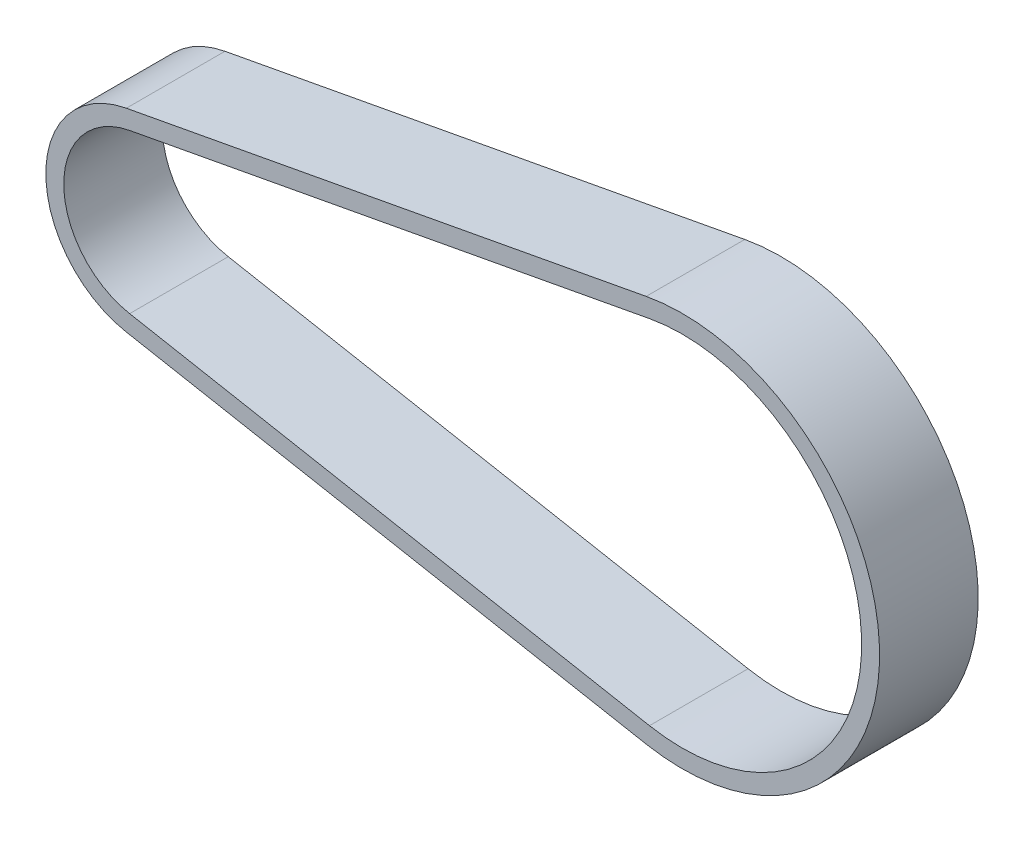
SolidWorks part; units mm, degrees
material "EPDM 60 硬度计"
ref_plane "前视基准面" through (0, 0, 0) normal (0, 0, 1) x (1, 0, 0)
ref_plane "上视基准面" through (0, 0, 0) normal (0, 1, 0) x (1, 0, 0)
ref_plane "右视基准面" through (0, 0, 0) normal (1, 0, 0) x (0, 0, -1)
other "Configuration Table"
sketch "草图1" plane through (0, 0, 0) normal (0, 0, 1) x (1, 0, 0)
  line L0 (-1000, 0) -> (49000, 0) construction
  line L1 (-62.0167, 10.8136) -> (-4.0333, 21.6271)
  line L2 (-62.0167, -10.8136) -> (-4.0333, -21.6271)
  line L3 (-61.65, 8.8475) -> (-3.6667, 19.661)
  line L4 (-61.65, -8.8475) -> (-3.6667, -19.661)
  arc A0 (-4.0333, -21.6271) -> (-4.0333, 21.6271) centre (0, 0) ccw
  arc A1 (-62.0167, 10.8136) -> (-62.0167, -10.8136) centre (-60, 0) ccw
  arc A2 (-3.6667, -19.661) -> (-3.6667, 19.661) centre (0, 0) ccw
  arc A3 (-61.65, 8.8475) -> (-61.65, -8.8475) centre (-60, 0) ccw
  dimension "D1" = 44
  dimension "D2" = 22
  dimension "D3" = 60
  dimension "D4" = 2
extrude "凸台-拉伸1" add sketch "草图1" along normal blind 11
